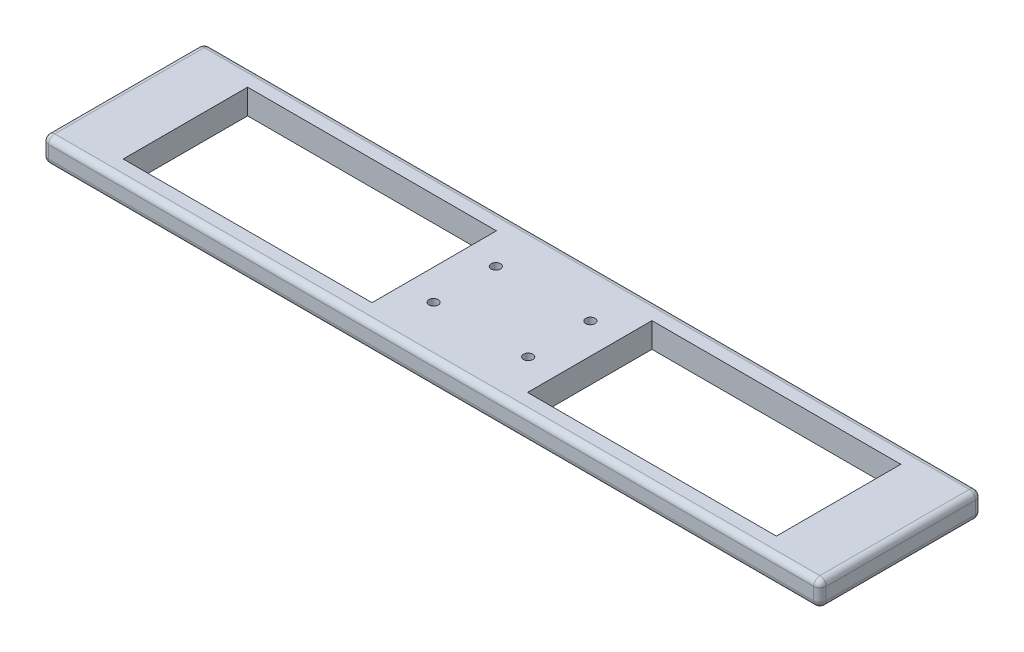
SolidWorks part; units mm, degrees
ref_plane "Front Plane" through (0, 0, 0) normal (0, 0, 1) x (1, 0, 0)
ref_plane "Top Plane" through (0, 0, 0) normal (0, 1, 0) x (1, 0, 0)
ref_plane "Right Plane" through (0, 0, 0) normal (1, 0, 0) x (0, 0, -1)
sketch "Sketch1" plane through (0, 0, 0) normal (0, 1, 0) x (1, 0, 0)
  line L1 (0, 0) -> (125, 0)
  line L2 (0, 0) -> (0, 26)
  line L3 (0, 26) -> (125, 26)
  line L4 (125, 0) -> (125, 26)
  dimension "D1" = 125
  dimension "D2" = 26
extrude "Boss-Extrude1" add sketch "Sketch1" along normal blind 4
sketch "Sketch2" plane through (0, 4, 0) normal (0, 1, 0) x (1, 0, 0)
  line L0 (125, 26) -> (0, 26) construction
  line L1 (50, 26) -> (75, 26)
  line L2 (50, 26) -> (50, 0)
  line L3 (50, 0) -> (75, 0)
  line L4 (75, 26) -> (75, 0)
  line L5 (0, 0) -> (125, 0) construction
  line L6 (125, 0) -> (125, 26) construction
  line L7 (10, 23) -> (50, 23)
  line L8 (10, 23) -> (10, 3)
  line L9 (10, 3) -> (50, 3)
  line L10 (50, 23) -> (50, 3)
  line L11 (75, 23) -> (115, 23)
  line L12 (75, 23) -> (75, 3)
  line L13 (75, 3) -> (115, 3)
  line L14 (115, 23) -> (115, 3)
  dimension "D1" = 25
  dimension "D2" = 50
  dimension "D3" = 40
  dimension "D4" = 40
  dimension "D5" = 20
  dimension "D6" = 20
  dimension "D7" = 3
  dimension "D8" = 3
extrude "Cut-Extrude1" cut sketch "Sketch2" against normal blind 4 contours L8 L9 L2 L7 | L14 L11 L4 L13
fillet "Fillet5" radius 1 12 edges at (125, 4, -13) (125, 2, 0) (125, 2, -26) (125, 0, -13) (62.5, 0, -26) (0, 2, -26) (62.5, 4, -26) (0, 0, -13) (62.5, 0, 0) (62.5, 4, 0) (0, 4, -13) (0, 2, 0)
sketch "Sketch3" plane through (0, 4, 0) normal (0, 1, 0) x (1, 0, 0)
  line L0 (50, 23) -> (75, 23) construction
  line L1 (75, 3) -> (50, 3) construction
  line L2 (50, 23) -> (50, 3) construction
  line L3 (75, 23) -> (75, 3) construction
  circle A0 centre (54.9, 18) radius 0.75
  circle A1 centre (70.1, 18) radius 0.75
  circle A2 centre (70.1, 8) radius 0.75
  circle A3 centre (54.9, 8) radius 0.75
  point P8 (54.9, 18)
  point P10 (70.1, 18)
  point P12 (70.1, 8)
  point P14 (54.9, 8)
  dimension "D1" = 1.5
  dimension "D4" = 5
  dimension "D2" = 4.9
  dimension "D3" = 5
  dimension "D5" = 4.9
hole_wizard "Ø1.5mm Dowel Hole1" positions "Sketch3" profile "Sketch4" hole size "Ø1.5" standard "ANSI Metric"
sketch "Sketch4" plane through (54.9, 4, -8) normal (1, 0, 0) x (0, 0, 1)
  line L0 (0, 0) -> (0, 8.4506)
  line L1 (0, 8.4506) -> (0.75, 8)
  line L2 (0.75, 8) -> (0.75, 0)
  line L5 (0.75, 0) -> (0, 0)
  line L10 (0, 8.4506) -> (-0.75, 8) construction
  line L11 (0, -6.35) -> (0, 107.95) construction
  dimension "Hole Dia." = 1.5
  dimension "Hole Depth" = 8
  dimension "Drill Angle" = 118
